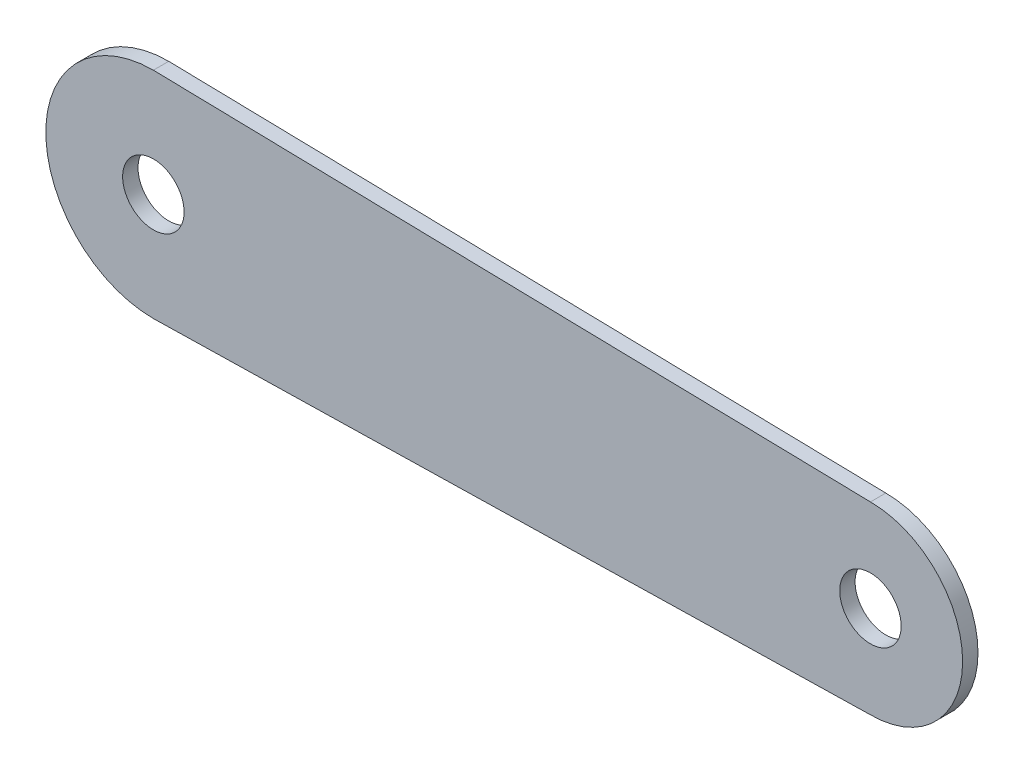
SolidWorks part; units mm, degrees
material "6061 Alloy"
ref_plane "Front Plane" through (0, 0, 0) normal (0, 0, 1) x (1, 0, 0)
ref_plane "Top Plane" through (0, 0, 0) normal (0, 1, 0) x (1, 0, 0)
ref_plane "Right Plane" through (0, 0, 0) normal (1, 0, 0) x (0, 0, -1)
sketch "Sketch1" plane through (0, 0, 0) normal (0, 0, 1) x (1, 0, 0)
  line L1 (-100, 35) -> (133.3333, 30)
  line L2 (133.3333, -30) -> (-100, -35)
  arc A0 (-100, 35) -> (-100, -35) centre (-100, 0) ccw
  arc A1 (133.3333, -30) -> (133.3333, 30) centre (133.3333, 0) ccw
  circle A2 centre (-100, 0) radius 10
  circle A3 centre (133.3333, 0) radius 10
extrude "Boss-Extrude1" add sketch "Sketch1" along normal blind 5
